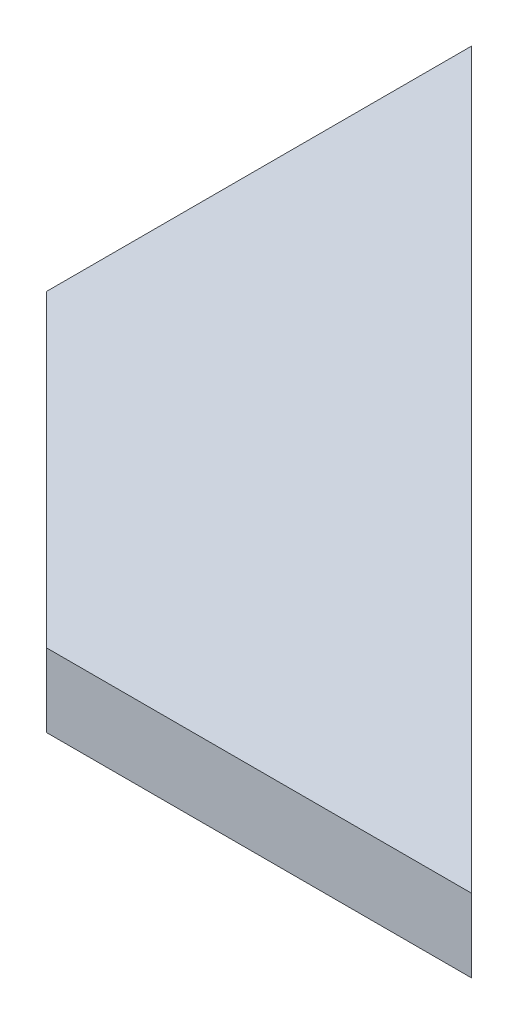
SolidWorks part; units mm, degrees
ref_plane "Front Plane" through (0, 0, 0) normal (0, 0, 1) x (1, 0, 0)
ref_plane "Top Plane" through (0, 0, 0) normal (0, 1, 0) x (1, 0, 0)
ref_plane "Right Plane" through (0, 0, 0) normal (1, 0, 0) x (0, 0, -1)
sketch "Sketch1" plane through (0, 0, 0) normal (0, 1, 0) x (1, 0, 0)
  line L0 (0, 0) -> (200, 0)
  line L1 (0, 0) -> (0, 200)
  line L2 (0, 200) -> (0, 84.0822)
  line L3 (200, 0) -> (84.0822, 0)
  line L4 (0, 84.0822) -> (84.0822, 0)
  line L5 (200, 0) -> (0, 200)
  point P6 (0, 14.6433)
  point P7 (0, 70.0487)
extrude "Boss-Extrude1" add sketch "Sketch1" along normal mid plane 20 contours L0 L5 L1 L4
